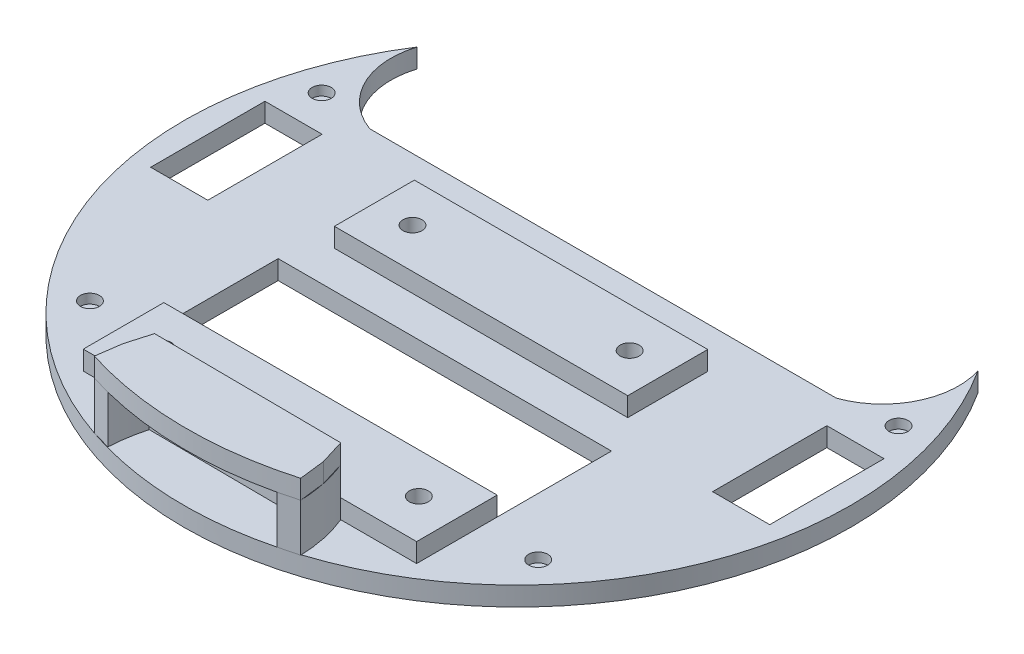
SolidWorks part; units mm, degrees
material "PBT General Purpose"
ref_plane "Front Plane" through (0, 0, 0) normal (0, 0, 1) x (1, 0, 0)
ref_plane "Top Plane" through (0, 0, 0) normal (0, 1, 0) x (1, 0, 0)
ref_plane "Right Plane" through (0, 0, 0) normal (1, 0, 0) x (0, 0, -1)
sketch "basedia" plane through (0, 0, 0) normal (0, 1, 0) x (1, 0, 0)
  circle A0 centre (0, 0) radius 175
  dimension "D1" = 350
sketch "Sketch2" plane through (0, 0, 0) normal (0, 1, 0) x (1, 0, 0)
  line L0 (0, -175) -> (0, 175) construction
  line L1 (-175, 0) -> (175, 0) construction
  line L3 (-87.5, -98.0764) -> (87.5, -98.0764)
  line L4 (-87.5, -98.0764) -> (87.5, -38.0764) construction
  line L5 (87.5, -38.0764) -> (-87.5, -38.0764)
  line L6 (87.5, -98.0764) -> (-87.5, -38.0764) construction
  line L7 (-87.5, -98.0764) -> (-87.5, -38.0764)
  line L8 (87.5, -38.0764) -> (87.5, -98.0764)
  line L9 (147.5, 0) -> (147.5, 30) construction
  line L10 (132.5, -30) -> (162.5, -30)
  line L11 (132.5, -30) -> (132.5, 30)
  line L12 (132.5, 30) -> (162.5, 30)
  line L13 (162.5, -30) -> (162.5, 30)
  line L14 (-132.5, -30) -> (-162.5, -30)
  line L15 (-162.5, -30) -> (-162.5, 30)
  line L16 (-132.5, -30) -> (-132.5, 30)
  line L17 (-132.5, 30) -> (-162.5, 30)
  line L18 (0, 0) -> (175, -175) construction
  line L19 (0, -175) -> (175, -175) construction
  line L20 (175, -175) -> (175, 0) construction
  line L21 (0, -175) -> (175, 0) construction
  line L22 (-158.941, 44.303) -> (158.941, 44.303)
  line L23 (-139.6503, 87.8794) -> (140.121, 87.127)
  line L24 (-123.7019, 93.3961) -> (123.7019, 93.3961)
  circle A0 centre (87.5, -87.5) radius 50
  circle A1 centre (-87.5, -87.5) radius 50
  arc A2 (158.941, 44.303) -> (140.121, 87.127) centre (0, 0) ccw
  arc A3 (-139.6503, 87.8794) -> (-158.941, 44.303) centre (0, 0) ccw
  circle A6 centre (0, 0) radius 123.7437 construction
  arc A7 (123.7019, 93.3961) -> (-123.7019, 93.3961) centre (0, 0) ccw
  circle A9 centre (0, 123.7437) radius 20
  point P0 (0, 30)
  point P3 (0, 0)
  point P6 (0, 0)
  point P11 (133.8009, 0)
  point P43 (0.2353, 87.5032)
  dimension "D1" = 60
  dimension "D2" = 175
  dimension "D3" = 60
  dimension "D4" = 30
  dimension "D5" = 30
sketch3d "3DSketch1"
  line L0 (162.5, 0, -30) -> (162.5, -30, -30)
  line L1 (132.5, 0, -30) -> (132.5, -30, -30)
  line L3 (162.5, 0, 30) -> (162.5, -29.7936, 30)
  line L7 (132.5, 0, 30) -> (132.5, -29.6372, 30)
  line L8 (-162.5, 0, 30) -> (-162.5, -29.7936, 30)
  line L9 (162.5, -30, -30) -> (162.5, -29.7936, 30)
  line L10 (162.5, -30, -30) -> (132.5, -30, -30)
  line L11 (132.5, -30, -30) -> (132.5, -29.6372, 30)
  line L12 (162.5, -29.7936, 30) -> (132.5, -29.6372, 30)
  line L13 (-132.5, 0, 30) -> (-132.5, -29.6372, 30)
  line L14 (-132.5, -30, -30) -> (-132.5, -29.6372, 30)
  line L15 (-162.5, -29.7936, 30) -> (-132.5, -29.6372, 30)
  line L16 (87.5, 0, 87.5) -> (87.5, -30, 87.5) construction
  line L17 (-162.5, -30, -30) -> (-162.5, -29.7936, 30)
  line L18 (-132.5, 0, -30) -> (-132.5, -30, -30)
  line L19 (-162.5, -30, -30) -> (-132.5, -30, -30)
  line L20 (-162.5, 0, -30) -> (-162.5, -30, -30)
  line L21 (77.1043, 0, 0) -> (-76.8957, 0, 0) construction
  line L22 (-0.4238, 0, -23.3789) -> (-0.4238, 0, 18.6211) construction
  line L23 (-0.4238, 0, -23.3789) -> (76.5762, 0, -23.3789)
  line L24 (76.5762, 0, -23.3789) -> (76.5762, 0, 18.6211)
  line L25 (76.5762, 0, 18.6211) -> (-77.4238, 0, 18.6211)
  line L26 (-77.4238, 0, 18.6211) -> (-77.4238, 0, -23.3789)
  line L27 (-0.4238, 0, -23.3789) -> (-77.4238, 0, -23.3789)
  line L28 (0, 0, 0) -> (0, 100, 0)
  point P24 (0.1043, 0, 0)
  point P28 (-0.4238, 0, -2.3789)
  dimension "D7" = 100
  dimension "D4" = 154
  dimension "D1" = 30
  dimension "D2" = 30
  dimension "D3" = 60.0004
  dimension "D5" = 42
  dimension "D6" = 30
extrude "Boss-Extrude1" add sketch "basedia" along normal blind 10
extrude "Cut-Extrude3" cut sketch "Sketch2" along normal up to surface (10 mm away) contours L8 L5 L7 L3 | L5 A0 L3 L8 | A1 L5 L7 L3
sketch "Sketch5" plane through (0, 10, 0) normal (0, 1, 0) x (1, 0, 0)
  line L0 (-122.466, 45) -> (122.466, 45)
  line L1 (-162.5, 30) -> (-132.5, 30)
  line L2 (-132.5, 30) -> (-132.5, -30)
  line L3 (-132.5, -30) -> (-162.5, -30)
  line L4 (-162.5, -30) -> (-162.5, 30)
  line L5 (132.5, -30) -> (132.5, 30)
  line L6 (132.5, 30) -> (162.5, 30)
  line L7 (162.5, 30) -> (162.5, -30)
  line L8 (162.5, -30) -> (132.5, -30)
  arc A0 (-147.2041, 94.6359) -> (147.2041, 94.6359) centre (0, 0) cw
  arc A1 (-147.2041, 94.6359) -> (-122.466, 45) centre (-109.0229, 82.6825) ccw
  arc A2 (122.466, 45) -> (147.2041, 94.6359) centre (109.0229, 82.6825) ccw
extrude "Cut-Extrude5" cut sketch "Sketch5" against normal blind 10
ref_plane "Plane1" through (0, 100, 0) normal (0, 1, 0) x (1, 0, 0)
sketch "Sketch6" plane through (0, 100, 0) normal (0, 1, 0) x (1, 0, 0)
  line L0 (-77.4238, -18.6211) -> (76.5762, -18.6211)
  line L1 (76.5762, -18.6211) -> (109.6085, -18.6211)
  line L2 (109.6085, -18.6211) -> (111.0376, 68.4299)
  line L3 (111.0376, 68.4299) -> (-0.1105, 68.4299)
  line L4 (-0.1105, 68.4299) -> (-0.4238, -18.6211) construction
  line L5 (-77.4218, -18.0669) -> (-110.4533, -17.8292)
  line L6 (-110.4533, -17.8292) -> (-111.2557, 69.2299)
  line L7 (-111.2557, 69.2299) -> (-0.1105, 68.4299)
sketch3d "3DSketch2"
  line L0 (111.0376, 100, -68.4299) -> (76.5762, 0, -23.3789)
  line L1 (109.6085, 100, 18.6211) -> (76.5762, 0, 18.6211)
  line L2 (-110.4533, 100, 17.8292) -> (-77.4238, 0, 18.6211)
  line L3 (-111.2557, 100, -69.2299) -> (-77.4238, 0, -23.3789)
sketch "Sketch7" plane through (0, 10, 0) normal (0, 1, 0) x (1, 0, 0)
  line L0 (-43.5651, -149.6749) -> (40.5596, -150.3197)
  line L1 (-50.8235, -139.619) -> (47.6507, -140.3737)
  line L2 (-46.5752, -168.4082) -> (-56.4275, -165.6531)
  line L3 (43.3107, -169.5559) -> (53.2793, -167.0306)
  arc A0 (-43.5651, -149.6749) -> (-46.5752, -168.4082) centre (38.5533, -172.4781) ccw
  arc A1 (40.5596, -150.3197) -> (43.3107, -169.5559) centre (-23.1444, -169.2449) cw
  arc A2 (47.6507, -140.3737) -> (53.2793, -167.0306) centre (-23.1444, -169.2449) cw
  arc A3 (-50.8235, -139.619) -> (-56.4275, -165.6531) centre (38.5533, -172.4781) ccw
  arc A4 (-50.8235, -139.619) -> (-56.5637, -167.9307) centre (38.5533, -172.4781) ccw construction
  arc A5 (47.6507, -140.3737) -> (53.3105, -169.6026) centre (-23.1444, -169.2449) cw construction
  dimension "D1" = 10
extrude "Boss-Extrude2" add sketch "Sketch7" along normal blind 25
sketch "Sketch8" plane through (0, 10, 0) normal (0, 1, 0) x (1, 0, 0)
  line L1 (-87.5, -98.0764) -> (87.5, -98.0764)
  line L2 (-87.5, -98.0764) -> (-87.5, -140.3737)
  line L3 (-87.5, -140.3737) -> (87.5, -140.3737)
  line L4 (87.5, -98.0764) -> (87.5, -140.3737)
  circle A0 centre (-67.5, -119.2251) radius 5
  circle A1 centre (67.5, -119.2251) radius 5
  dimension "D1" = 20
  dimension "D2" = 20
extrude "Boss-Extrude3" add sketch "Sketch8" along normal blind 10
sketch "Sketch9" plane through (0, 10, 0) normal (0, 1, 0) x (1, 0, 0)
  line L0 (-77.4238, 23.3789) -> (76.5762, 23.3789)
  line L1 (76.5762, 23.3789) -> (76.5762, -18.6211)
  line L2 (76.5762, -18.6211) -> (-77.4238, -18.6211)
  line L3 (-77.4238, -18.6211) -> (-77.4238, 23.3789)
  circle A0 centre (-57.4238, 2.3789) radius 5
  circle A1 centre (56.5762, 2.3789) radius 5
  dimension "D1" = 20
  dimension "D2" = 20
extrude "Boss-Extrude4" add sketch "Sketch9" along normal blind 10
sketch "Sketch10" plane through (0, 10, 0) normal (0, 1, 0) x (1, 0, 0)
  line L0 (0, 0) -> (0, 103.306) construction
  circle A0 centre (-117.6657, -106.7049) radius 5
  circle A1 centre (-151.4263, 48.6932) radius 5
  circle A2 centre (151.4263, 48.6932) radius 5
  circle A3 centre (117.6657, -106.7049) radius 5
extrude "Cut-Extrude6" cut sketch "Sketch10" against normal blind 5
sketch "Sketch11" plane through (0, 0, -45) normal (0, 0, -1) x (-1, 0, 0)
  line L1 (-112.0415, 6.7402) -> (-52.0415, 6.7402)
  line L2 (-112.0415, 6.7402) -> (-112.0415, 3.7402)
  line L3 (-112.0415, 3.7402) -> (-52.0415, 3.7402)
  line L4 (-52.0415, 6.7402) -> (-52.0415, 3.7402)
  line L5 (52.0415, 6.7402) -> (112.0415, 6.7402)
  line L6 (52.0415, 6.7402) -> (52.0415, 3.7402)
  line L7 (52.0415, 3.7402) -> (112.0415, 3.7402)
  line L8 (112.0415, 6.7402) -> (112.0415, 3.7402)
extrude "Cut-Extrude7" cut sketch "Sketch11" against normal blind 10
sketch "Sketch12" plane through (0, 35, 0) normal (0, 1, 0) x (1, 0, 0)
  line L0 (-50.8235, -139.619) -> (47.6507, -140.3737)
  line L1 (-50.8235, -139.619) -> (-54.5401, -152.4392)
  line L2 (-54.5401, -152.4392) -> (-56.4275, -165.6531)
  line L3 (47.6507, -140.3737) -> (51.6619, -153.4495)
  line L4 (51.6619, -153.4495) -> (53.2793, -167.0306)
  arc A0 (-56.4275, -165.6531) -> (53.2793, -167.0306) centre (0.7179, 16.1874) ccw
extrude "Boss-Extrude5" add sketch "Sketch12" along normal blind 10
